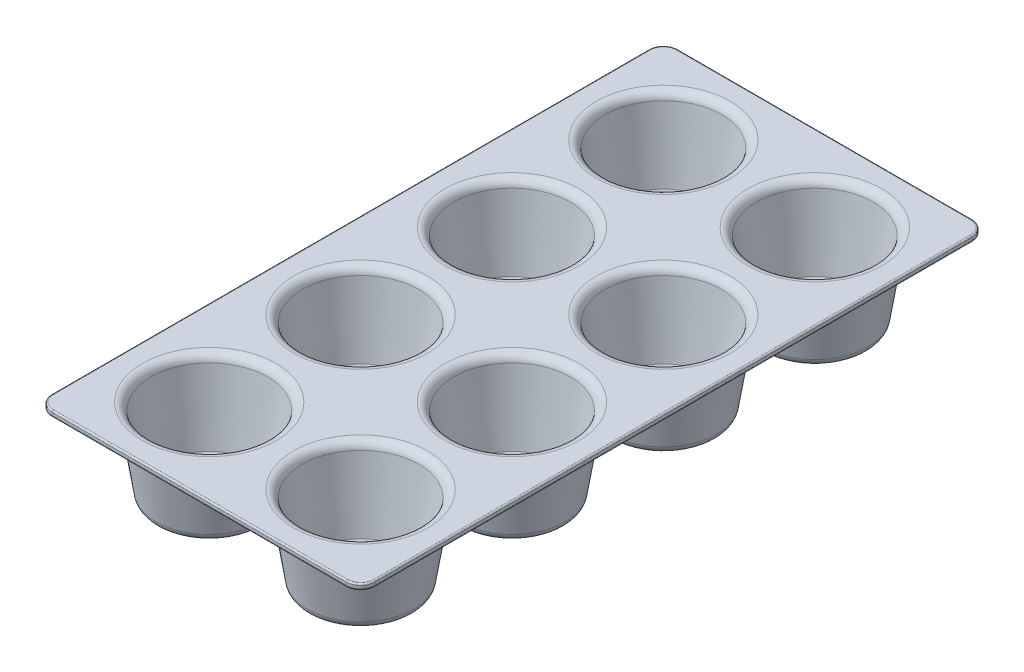
SolidWorks part; units mm, degrees
material "AISI 1015 Steel, Cold Drawn (SS)"
ref_plane "Front Plane" through (0, 0, 0) normal (0, 0, 1) x (1, 0, 0)
ref_plane "Top Plane" through (0, 0, 0) normal (0, 1, 0) x (1, 0, 0)
ref_plane "Right Plane" through (0, 0, 0) normal (1, 0, 0) x (0, 0, -1)
sketch "Sketch1" plane through (0, 0, 0) normal (1, 0, 0) x (0, 0, -1)
  line L0 (0, 0) -> (0, -58) construction
  line L1 (0, -58) -> (-30.6146, -58)
  line L2 (-36.5407, -52.9386) -> (-44.0246, -5.6871)
  line L4 (-40.0739, -5.0614) -> (-32.59, -52.3129)
  line L5 (-30.6146, -54) -> (0, -54)
  line L6 (0, -54) -> (0, -58)
  line L7 (-46, 0) -> (-47, 0)
  line L8 (-47, 0) -> (-47, -4)
  line L9 (-47, -4) -> (-46, -4)
  arc A0 (-30.6146, -58) -> (-36.5407, -52.9386) centre (-30.6146, -52) cw
  arc A1 (-32.59, -52.3129) -> (-30.6146, -54) centre (-30.6146, -52) ccw
  arc A2 (-40.0739, -5.0614) -> (-46, 0) centre (-46, -6) ccw
  arc A3 (-46, -4) -> (-44.0246, -5.6871) centre (-46, -6) cw
  dimension "D3" = 6
  dimension "D6" = 6
  dimension "D4" = 4
  dimension "D1" = 58
  dimension "D2" = 92
  dimension "D7" = 1
  dimension "D5" = 9
revolve "Revolve1" add sketch "Sketch1" angle 360 about L0
pattern_linear "LPattern1" count 2 spacing 104 along (1, 0, 0) count 4 spacing 104 along (0, 0, 1) of bodies 101
sketch "Sketch2" plane through (0, 0, 0) normal (0, 1, 0) x (1, 0, 0)
  line L0 (0, 0) -> (104, 0) construction
  line L1 (-49, -371) -> (153, -371)
  line L2 (-59, -361) -> (-59, 49)
  line L3 (-49, 59) -> (153, 59)
  line L4 (163, -361) -> (163, 49)
  line L5 (52, 0) -> (52, 59) construction
  line L6 (0, 0) -> (0, -312) construction
  line L7 (0, -156) -> (-59, -156) construction
  line L8 (0, 47) -> (0, 59) construction
  line L9 (-47, 0) -> (-59, 0) construction
  circle A0 centre (104, 0) radius 30.6146 construction
  circle A1 centre (0, 0) radius 30.6146 construction
  circle A2 centre (0, -312) radius 47 construction
  circle A3 centre (104, -312) radius 47 construction
  circle A4 centre (104, -208) radius 47 construction
  circle A5 centre (0, -208) radius 47 construction
  circle A6 centre (0, -104) radius 47 construction
  circle A7 centre (104, -104) radius 47 construction
  circle A8 centre (104, 0) radius 47 construction
  circle A9 centre (0, 0) radius 47 construction
  circle A10 centre (0, -312) radius 47
  circle A11 centre (104, -312) radius 47
  arc A24 (-59, 49) -> (-49, 59) centre (-49, 49) cw
  arc A25 (153, 59) -> (163, 49) centre (153, 49) cw
  arc A26 (153, -371) -> (163, -361) centre (153, -361) ccw
  arc A27 (-49, -371) -> (-59, -361) centre (-49, -361) cw
  circle A28 centre (104, -208) radius 47
  circle A30 centre (0, -208) radius 47
  circle A31 centre (0, -104) radius 47
  circle A32 centre (104, -104) radius 47
  circle A33 centre (104, 0) radius 47
  circle A34 centre (0, 0) radius 47
  point P42 (52, 59)
  point P45 (-59, -156)
  dimension "D1" = 10
  dimension "D2" = 12
extrude "Boss-Extrude1" add sketch "Sketch2" against normal blind 4
fillet "Fillet1" radius 1 16 edges at (52, 0, -59) (160.0711, 0, -56.0711) (163, 0, 156) (160.0711, 0, 368.0711) (52, 0, 371) (-56.0711, 0, 368.0711) (-59, 0, 156) (-56.0711, 0, -56.0711) (-59, -4, 156) (-56.0711, -4, 368.0711) (52, -4, 371) (160.0711, -4, 368.0711) (163, -4, 156) (160.0711, -4, -56.0711) (52, -4, -59) (-56.0711, -4, -56.0711)
equation "\"A\"= 4"
equation "\"D1@Boss-Extrude1\"=\"A\""
equation "\"D4@Sketch1\"=\"A\""
equation "\"B\"= 92"
equation "\"C\"= 12"
equation "\"D4@LPattern1\"=\"C\"+\"B\""
equation "\"D3@LPattern1\"=\"B\"+\"C\""
equation "\"D2@Sketch1\"=\"B\""
equation "\"D2@Sketch2\"=\"C\""
